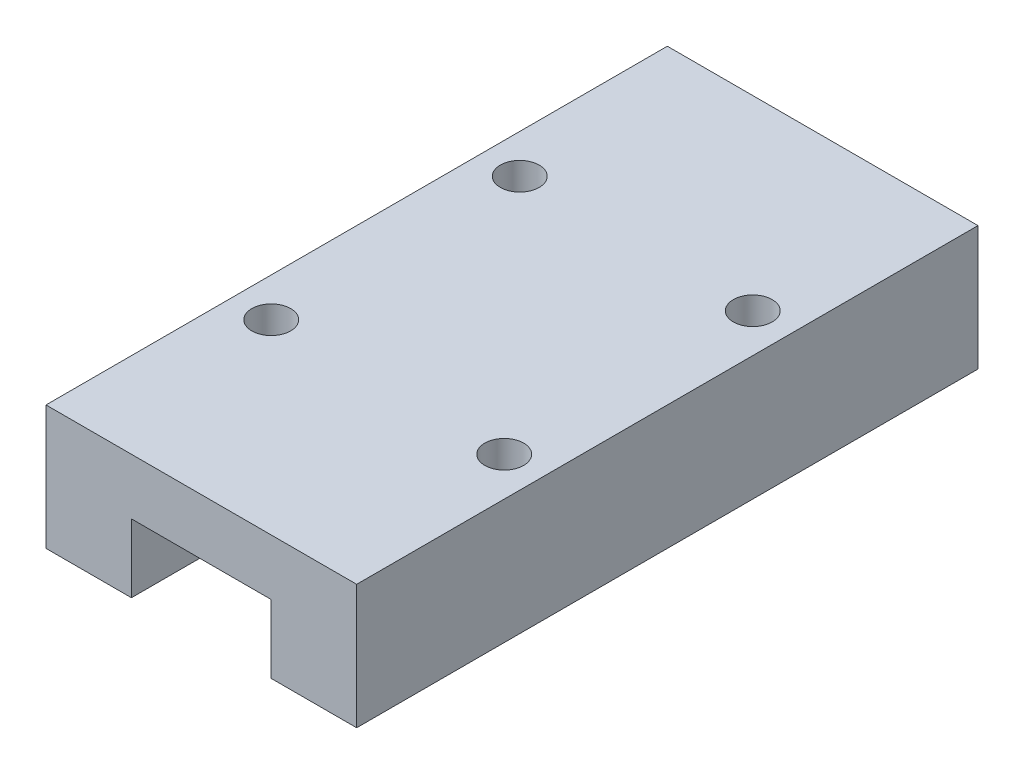
SolidWorks part; units mm, degrees
ref_plane "Front Plane" through (0, 0, 0) normal (0, 0, 1) x (1, 0, 0)
ref_plane "Top Plane" through (0, 0, 0) normal (0, 1, 0) x (1, 0, 0)
ref_plane "Right Plane" through (0, 0, 0) normal (1, 0, 0) x (0, 0, -1)
sketch "Sketch1" plane through (0, 0, 0) normal (0, 0, 1) x (1, 0, 0)
  line L0 (0, 0) -> (5.5, 0)
  line L1 (0, 0) -> (20, 0) construction
  line L2 (0, 0) -> (0, 8)
  line L3 (0, 8) -> (20, 8)
  line L4 (20, 0) -> (20, 8)
  line L7 (5.5, 0) -> (5.5, 4.4)
  line L8 (5.5, 4.4) -> (14.5, 4.4)
  line L9 (14.5, 4.4) -> (14.5, 0)
  line L12 (14.5, 0) -> (20, 0)
  line L13 (10, 8) -> (10, 0) construction
  point P7 (5.5, 0.1927)
  point P15 (0, 0)
  point P16 (0, 0)
  point P17 (0, 0)
  point P18 (13.0818, 2.1128)
  point P19 (13.0613, 1.6814)
  point P20 (12.0751, 1.1472)
  point P21 (15.5, 3.0863)
  dimension "D1" = 20
  dimension "D2" = 8
  dimension "D3" = 3.6
  dimension "D4" = 9
extrude "Boss-Extrude1" add sketch "Sketch1" along normal blind 40
sketch "Sketch2" plane through (0, 8, 0) normal (0, 1, 0) x (1, 0, 0)
  line L0 (10, -40) -> (10, 0) construction
  line L1 (20, -40) -> (0, -40) construction
  line L2 (20, 0) -> (0, 0) construction
  line L3 (17.5, 0) -> (17.5, -40) construction
  line L4 (2.5, -40) -> (2.5, 0) construction
  line L5 (0, -20) -> (20, -20) construction
  line L6 (0, -40) -> (0, 0) construction
  line L7 (20, -40) -> (20, 0) construction
  circle A0 centre (2.5, -12) radius 1.25
  circle A1 centre (17.5, -12) radius 1.25
  circle A2 centre (17.5, -28) radius 1.25
  circle A3 centre (2.5, -28) radius 1.25
  dimension "D3" = 2.5
  dimension "D1" = 15
  dimension "D2" = 8
extrude "Cut-Extrude1" cut sketch "Sketch2" against normal blind 5
